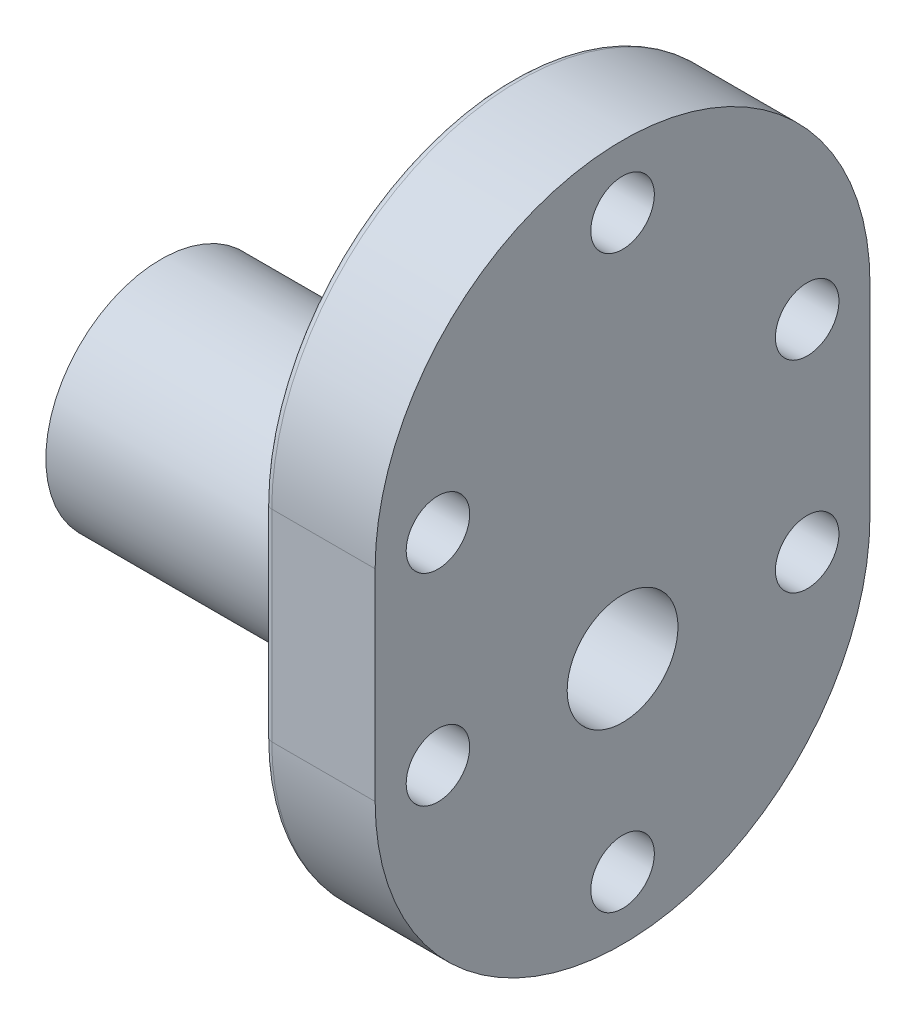
SolidWorks part; units mm, degrees
ref_plane "Front Plane" through (0, 0, 0) normal (0, 0, 1) x (1, 0, 0)
ref_plane "Top Plane" through (0, 0, 0) normal (0, 1, 0) x (1, 0, 0)
ref_plane "Right Plane" through (0, 0, 0) normal (1, 0, 0) x (0, 0, -1)
sketch "Sketch1" plane through (0, 0, 0) normal (1, 0, 0) x (0, 0, -1)
  line L0 (-85.1, 69.32) -> (-85.1, 0)
  line L1 (85.1, 69.32) -> (85.1, 0)
  arc A0 (-85.1, 0) -> (85.1, 0) centre (0, 0) ccw
  arc A1 (85.1, 69.32) -> (-85.1, 69.32) centre (0, 69.32) ccw
  dimension "D1" = 170.2
  dimension "D2" = 69.32
extrude "Boss-Extrude1" add sketch "Sketch1" against normal blind 38.1
sketch "Sketch2" plane through (-38.1, 0, 0) normal (-1, 0, 0) x (0, 0, 1)
  circle A0 centre (0, 0) radius 39.62
  dimension "D1" = 79.24
extrude "Boss-Extrude2" add sketch "Sketch2" along normal blind 120.65
hole_wizard "1/16 (1.25) Diameter Hole1" positions "3DSketch1" profile "Sketch3" hole size "1/16" standard "ANSI Inch"
sketch3d "3DSketch1"
  line L0 (-158.75, 0, 0) -> (-38.1, 0, 0) construction
  point P0 (-158.75, 0, 0)
sketch "Sketch3" plane through (-158.75, 0, 0) normal (0, 1, 0) x (0, 0, 1)
  line L0 (0, 0) -> (0, 76.2)
  line L1 (0, 76.2) -> (15.875, 71.9463)
  line L2 (15.875, 71.9463) -> (15.875, 0)
  line L5 (15.875, 0) -> (0, 0)
  line L10 (0, 76.2) -> (-15.875, 71.9463) construction
  line L11 (0, -6.35) -> (0, 107.95) construction
  dimension "Hole Dia." = 31.75
  dimension "Hole Depth" = 76.2
  dimension "Drill Angle" = 150
sketch "Sketch4" plane through (-158.75, 0, 0) normal (-1, 0, 0) x (0, 0, 1)
  circle A0 centre (0, 0) radius 19.05
  dimension "D1" = 38.1
extrude "Cut-Extrude1" cut sketch "Sketch4" against normal through all
fillet "Fillet1" radius 3.81 1 edges at (-38.1, 0, -39.62)
sketch "Sketch6" plane through (-38.1, 0, 0) normal (-1, 0, 0) x (0, 0, 1)
  line L0 (-85.1, 34.66) -> (85.1, 34.66) construction
  line L1 (-85.1, 0) -> (-85.1, 69.32) construction
  line L2 (85.1, 69.32) -> (85.1, 0) construction
  line L3 (0, 154.42) -> (0, 34.66) construction
  arc A0 (85.1, 69.32) -> (-85.1, 69.32) centre (0, 69.32) ccw construction
  circle A1 centre (0, 132.831) radius 10.922
  circle A2 centre (63.5, 69.331) radius 10.922
  circle A3 centre (-63.5, 69.331) radius 10.922
  circle A4 centre (63.5, -0.011) radius 10.922
  circle A5 centre (0, -63.511) radius 10.922
  circle A6 centre (-63.5, -0.011) radius 10.922
  dimension "D1" = 21.844
  dimension "D2" = 63.5
  dimension "D3" = 63.5
  dimension "D4" = 69.342
extrude "Cut-Extrude2" cut sketch "Sketch6" against normal through all
fillet "Fillet2" radius 2.54 4 edges at (-38.1, 34.66, -85.1) (-38.1, -85.1, 0) (-38.1, 34.66, 85.1) (-38.1, 154.42, 0)
hole_wizard "1/16 (2.5) Diameter Hole1" positions "3DSketch3" profile "Sketch8" hole size "1/16" standard "ANSI Inch"
sketch3d "3DSketch3"
  line L0 (0, 0, 0) -> (-158.75, 0, 0) construction
  point P0 (-158.75, 0, 0)
sketch "Sketch8" plane through (-158.75, 0, 0) normal (0, 1, 0) x (0, 0, 1)
  line L0 (0, 0) -> (0, 76.2)
  line L1 (0, 76.2) -> (31.75, 67.6926)
  line L2 (31.75, 67.6926) -> (31.75, 0)
  line L5 (31.75, 0) -> (0, 0)
  line L10 (0, 76.2) -> (-31.75, 67.6926) construction
  line L11 (0, -6.35) -> (0, 107.95) construction
  dimension "Hole Dia." = 63.5
  dimension "Hole Depth" = 76.2
  dimension "Drill Angle" = 150
